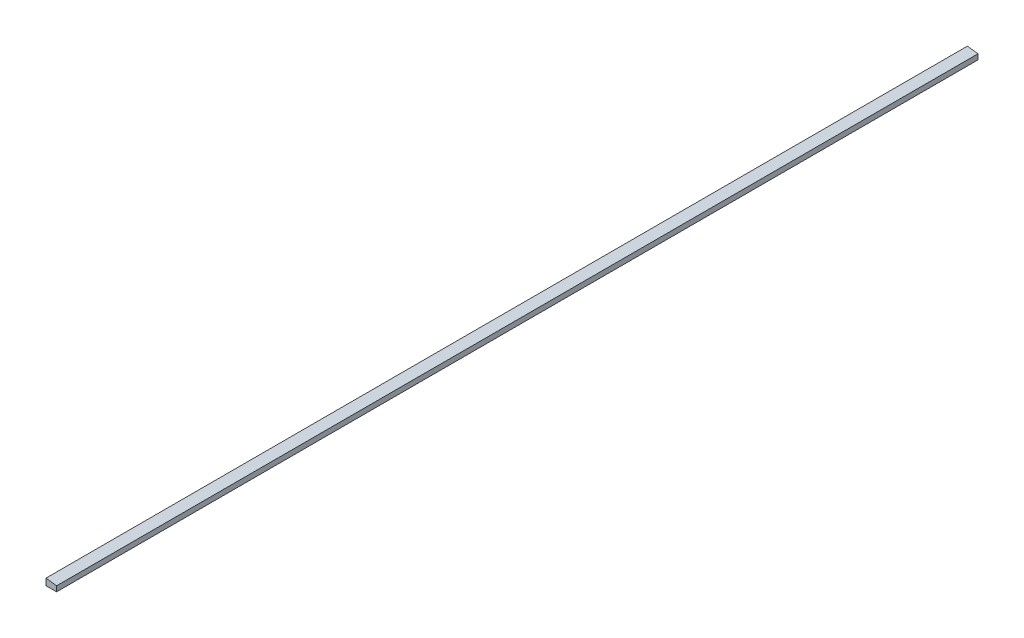
SolidWorks part; units mm, degrees
ref_plane "Ebene vorne" through (0, 0, 0) normal (0, 0, 1) x (1, 0, 0)
ref_plane "Ebene oben" through (0, 0, 0) normal (0, 1, 0) x (1, 0, 0)
ref_plane "Ebene rechts" through (0, 0, 0) normal (1, 0, 0) x (0, 0, -1)
sketch "Skizze1" plane through (0, 0, 0) normal (0, 0, 1) x (1, 0, 0)
  line L1 (0, 0) -> (8, 0)
  line L2 (0, 0) -> (0, 5)
  line L3 (0, 5) -> (8, 5)
  line L4 (8, 0) -> (8, 5)
  dimension "D1" = 5
  dimension "D2" = 8
extrude "Aufsatz-Linear austragen1" add sketch "Skizze1" along normal blind 695
sketch "Skizze2" plane through (0, 0, 695) normal (0, 0, 1) x (1, 0, 0)
  line L0 (0, 5) -> (8, 4)
  line L1 (8, 0) -> (8, 5) construction
  line L2 (8, 4) -> (8, 5)
  line L3 (8, 5) -> (0, 5)
  dimension "D1" = 1
extrude "Schnitt-Linear austragen1" cut sketch "Skizze2" against normal through all
